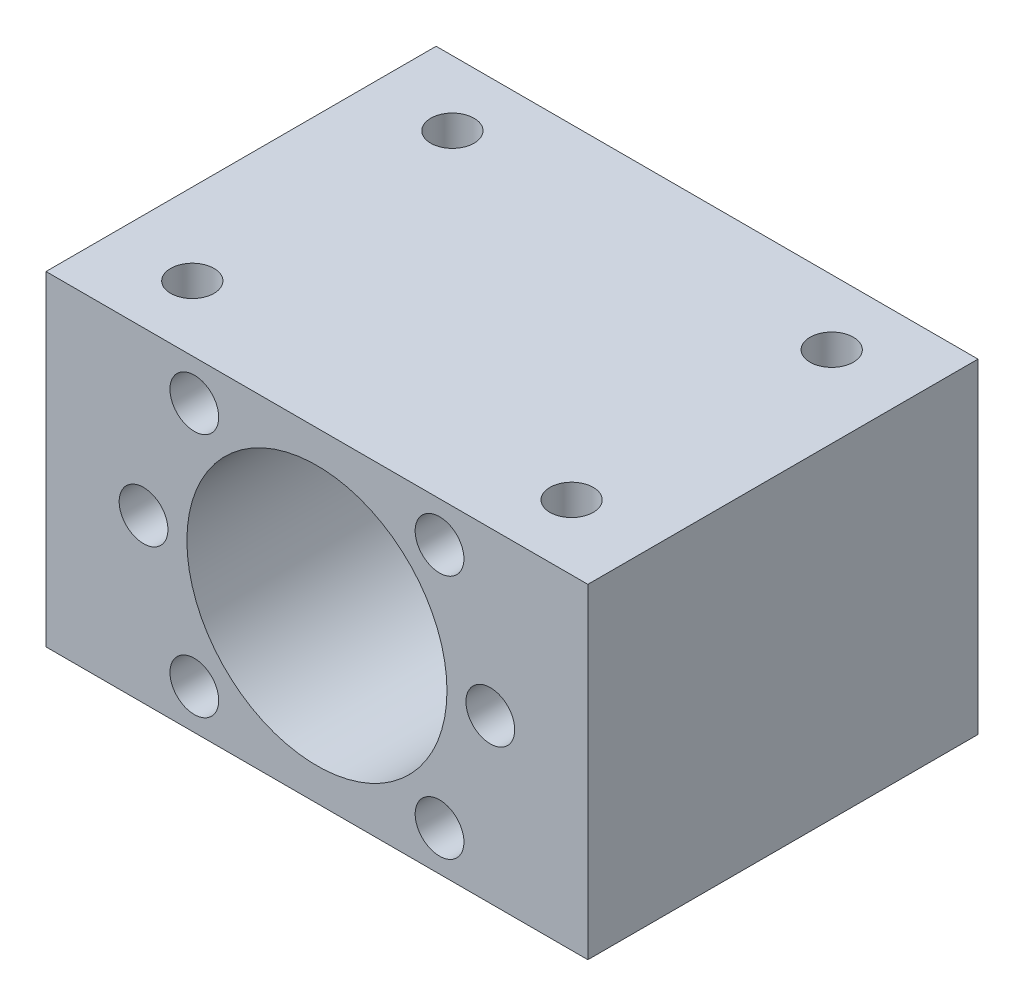
SolidWorks part; units mm, degrees
material "6061 合金"
ref_plane "前视基准面" through (0, 0, 0) normal (0, 0, 1) x (1, 0, 0)
ref_plane "上视基准面" through (0, 0, 0) normal (0, 1, 0) x (1, 0, 0)
ref_plane "右视基准面" through (0, 0, 0) normal (1, 0, 0) x (0, 0, -1)
other "Configuration Table"
sketch "草图1" plane through (0, 0, 0) normal (0, 0, 1) x (1, 0, 0)
  line L0 (25, 15) -> (-25, 15)
  line L1 (-25, 15) -> (-25, -15)
  line L2 (-25, -15) -> (25, -15)
  line L3 (25, -15) -> (25, 15)
  circle A0 centre (-11.3137, 11.3137) radius 2.25
  circle A1 centre (-16, 0) radius 2.25
  circle A2 centre (-11.3137, -11.3137) radius 2.25
  circle A3 centre (11.3137, -11.3137) radius 2.25
  circle A4 centre (16, 0) radius 2.25
  circle A5 centre (11.3137, 11.3137) radius 2.25
  circle A6 centre (0, 0) radius 12
extrude "凸台-拉伸1" add sketch "草图1" along normal blind 36
sketch "草图2" plane through (0, 15, 0) normal (0, 1, 0) x (1, 0, 0)
  line L0 (25, -18) -> (-43.8119, -18) construction
  line L1 (25, -36) -> (25, 0) construction
  line L2 (-25, -36) -> (25, -36) construction
  line L3 (0, -36) -> (0, 32.9428) construction
  line L4 (25, -36) -> (25, 0) construction
  circle A0 centre (17.5, -30) radius 2
  circle A3 centre (-17.5, -30) radius 2
  circle A4 centre (-17.5, -6) radius 2
  circle A5 centre (17.5, -6) radius 2
  dimension "D1" = 6
  dimension "D2" = 7.5
  dimension "D3" = 4
extrude "切除-拉伸1" cut sketch "草图2" against normal blind 10.2
